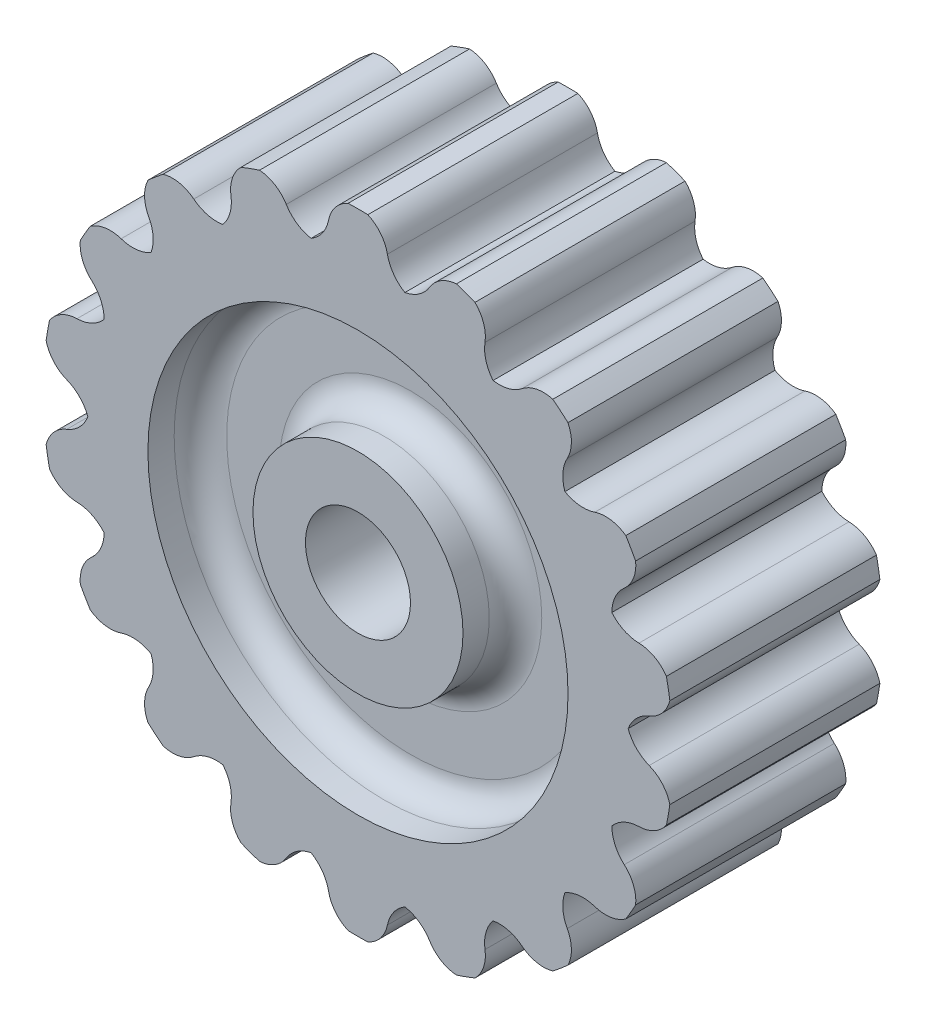
SolidWorks part; units mm, degrees
ref_plane "Front Plane" through (0, 0, 0) normal (0, 0, 1) x (1, 0, 0)
ref_plane "Top Plane" through (0, 0, 0) normal (0, 1, 0) x (1, 0, 0)
ref_plane "Right Plane" through (0, 0, 0) normal (1, 0, 0) x (0, 0, -1)
sketch "Sketch1" plane through (0, 0, 0) normal (1, 0, 0) x (0, 0, -1)
  line L0 (-45.5018, 0) -> (45.5018, 0) construction
  line L1 (0, 44.1006) -> (0, -44.1006) construction
  line L2 (-12.7, 6.35) -> (-12.7, 12.7)
  line L3 (-12.7, 12.7) -> (-9.525, 12.7)
  line L4 (-9.525, 12.7) -> (-9.525, 25.4)
  line L5 (-9.525, 25.4) -> (-12.7, 25.4)
  line L6 (-12.7, 25.4) -> (-12.7, 38.1)
  line L7 (-12.7, 38.1) -> (12.7, 38.1)
  line L8 (-12.7, 6.35) -> (12.7, 6.35)
  line L9 (-26.9876, 19.05) -> (7.3019, 19.05) construction
  line L10 (-6.35, 15.875) -> (-6.35, 22.225)
  line L11 (6.35, 15.875) -> (6.35, 22.225)
  line L12 (12.7, 25.4) -> (12.7, 38.1)
  line L13 (9.525, 25.4) -> (12.7, 25.4)
  line L14 (9.525, 12.7) -> (9.525, 25.4)
  line L15 (12.7, 12.7) -> (9.525, 12.7)
  line L16 (12.7, 6.35) -> (12.7, 12.7)
  arc A0 (-9.525, 25.4) -> (-6.35, 22.225) centre (-9.525, 22.225) cw
  arc A1 (-9.525, 12.7) -> (-6.35, 15.875) centre (-9.525, 15.875) ccw
  arc A2 (9.525, 12.7) -> (6.35, 15.875) centre (9.525, 15.875) cw
  arc A3 (9.525, 25.4) -> (6.35, 22.225) centre (9.525, 22.225) ccw
  point P4 (0, 0)
  point P8 (0, 0)
  point P15 (0, 6.35)
  point P18 (-6.35, 14.6295)
  point P22 (0, 44.1006)
  point P33 (0, 38.1)
  dimension "D4" = 3.175
  dimension "D7" = 6.35
  dimension "D9" = 3.175
  dimension "D1" = 6.35
  dimension "D2" = 25.4
  dimension "D3" = 6.35
  dimension "D5" = 25.4
  dimension "D6" = 12.7
  dimension "D8" = 12.7
  dimension "D10" = 12.7
revolve "Revolve1" add sketch "Sketch1" angle 360 about L0
sketch "Sketch2" plane through (0, 0, 12.7) normal (0, 0, 1) x (1, 0, 0)
  line L0 (0, 62.3351) -> (0, 0) construction
  circle A0 centre (0, 0) radius 32.6644
  circle A1 centre (0, 0) radius 35.306
  circle A2 centre (0, 0) radius 38.1 construction
  arc A3 (-5.6721, 32.1682) -> (-3.56, 35.1261) centre (-7.9287, 36.0125) ccw
  arc A4 (-3.56, 35.1261) -> (-1.1938, 38.0813) centre (0.4965, 34.303) cw
  arc A5 (3.56, 35.1261) -> (1.1938, 38.0813) centre (-0.4965, 34.303) ccw
  arc A6 (5.6721, 32.1682) -> (3.56, 35.1261) centre (7.9287, 36.0125) cw
  arc A7 (5.6721, 32.1682) -> (8.6685, 34.2253) centre (4.8665, 36.5524) ccw
  arc A8 (8.6685, 34.2253) -> (11.9028, 36.193) centre (12.1989, 32.0645) cw
  arc A9 (15.3591, 31.7901) -> (14.1464, 35.3764) centre (11.2658, 32.4041) ccw
  arc A10 (16.3322, 28.2882) -> (15.3591, 31.7901) centre (19.7675, 31.1289) cw
  arc A11 (16.3322, 28.2882) -> (19.8515, 29.1965) centre (17.0747, 32.6836) ccw
  arc A12 (19.8515, 29.1965) -> (23.5637, 29.9393) centre (22.4299, 25.9585) cw
  arc A13 (25.3057, 24.6198) -> (25.3927, 28.4046) centre (21.6692, 26.5967) ccw
  arc A14 (25.0224, 20.9963) -> (25.3057, 24.6198) centre (29.2221, 22.4907) cw
  arc A15 (25.0224, 20.9963) -> (28.64, 20.6461) centre (27.2234, 24.8726) ccw
  arc A16 (28.64, 20.6461) -> (32.3825, 20.0745) centre (29.9555, 16.7215) cw
  arc A17 (32.2001, 14.48) -> (33.5763, 18.0068) centre (29.459, 17.5815) ccw
  arc A18 (30.6945, 11.1719) -> (32.2001, 14.48) centre (35.152, 11.1398) cw
  arc A19 (30.6945, 11.1719) -> (33.9742, 9.6055) centre (34.0886, 14.0617) ccw
  arc A20 (33.9742, 9.6055) -> (37.2955, 7.7884) centre (33.8681, 5.4677) cw
  arc A21 (35.2106, 2.5936) -> (37.7101, 5.4371) centre (33.6956, 6.4456) ccw
  arc A22 (32.6644, 0) -> (35.2106, 2.5936) centre (36.8422, -1.5547) cw
  arc A23 (32.6644, 0) -> (35.2106, -2.5936) centre (36.8422, 1.5547) ccw
  arc A24 (35.2106, -2.5936) -> (37.7101, -5.4371) centre (33.6956, -6.4456) cw
  arc A25 (33.9742, -9.6055) -> (37.2955, -7.7884) centre (33.8681, -5.4677) ccw
  arc A26 (30.6945, -11.1719) -> (33.9742, -9.6055) centre (34.0886, -14.0617) cw
  arc A27 (30.6945, -11.1719) -> (32.2001, -14.48) centre (35.152, -11.1398) ccw
  arc A28 (32.2001, -14.48) -> (33.5763, -18.0068) centre (29.459, -17.5815) cw
  arc A29 (28.64, -20.6461) -> (32.3825, -20.0745) centre (29.9555, -16.7215) ccw
  arc A30 (25.0224, -20.9963) -> (28.64, -20.6461) centre (27.2234, -24.8726) cw
  arc A31 (25.0224, -20.9963) -> (25.3057, -24.6198) centre (29.2221, -22.4907) ccw
  arc A32 (25.3057, -24.6198) -> (25.3927, -28.4046) centre (21.6692, -26.5967) cw
  arc A33 (19.8515, -29.1965) -> (23.5637, -29.9393) centre (22.4299, -25.9585) ccw
  arc A34 (16.3322, -28.2882) -> (19.8515, -29.1965) centre (17.0747, -32.6836) cw
  arc A35 (16.3322, -28.2882) -> (15.3591, -31.7901) centre (19.7675, -31.1289) ccw
  arc A36 (15.3591, -31.7901) -> (14.1464, -35.3764) centre (11.2658, -32.4041) cw
  arc A37 (8.6685, -34.2253) -> (11.9028, -36.193) centre (12.1989, -32.0645) ccw
  arc A38 (5.6721, -32.1682) -> (8.6685, -34.2253) centre (4.8665, -36.5524) cw
  arc A39 (5.6721, -32.1682) -> (3.56, -35.1261) centre (7.9287, -36.0125) ccw
  arc A40 (3.56, -35.1261) -> (1.1938, -38.0813) centre (-0.4965, -34.303) cw
  arc A41 (-3.56, -35.1261) -> (-1.1938, -38.0813) centre (0.4965, -34.303) ccw
  arc A42 (-5.6721, -32.1682) -> (-3.56, -35.1261) centre (-7.9287, -36.0125) cw
  arc A43 (-5.6721, -32.1682) -> (-8.6685, -34.2253) centre (-4.8665, -36.5524) ccw
  arc A44 (-8.6685, -34.2253) -> (-11.9028, -36.193) centre (-12.1989, -32.0645) cw
  arc A45 (-15.3591, -31.7901) -> (-14.1464, -35.3764) centre (-11.2658, -32.4041) ccw
  arc A46 (-16.3322, -28.2882) -> (-15.3591, -31.7901) centre (-19.7675, -31.1289) cw
  arc A47 (-16.3322, -28.2882) -> (-19.8515, -29.1965) centre (-17.0747, -32.6836) ccw
  arc A48 (-19.8515, -29.1965) -> (-23.5637, -29.9393) centre (-22.4299, -25.9585) cw
  arc A49 (-25.3057, -24.6198) -> (-25.3927, -28.4046) centre (-21.6692, -26.5967) ccw
  arc A50 (-25.0224, -20.9963) -> (-25.3057, -24.6198) centre (-29.2221, -22.4907) cw
  arc A51 (-25.0224, -20.9963) -> (-28.64, -20.6461) centre (-27.2234, -24.8726) ccw
  arc A52 (-28.64, -20.6461) -> (-32.3825, -20.0745) centre (-29.9555, -16.7215) cw
  arc A53 (-32.2001, -14.48) -> (-33.5763, -18.0068) centre (-29.459, -17.5815) ccw
  arc A54 (-30.6945, -11.1719) -> (-32.2001, -14.48) centre (-35.152, -11.1398) cw
  arc A55 (-30.6945, -11.1719) -> (-33.9742, -9.6055) centre (-34.0886, -14.0617) ccw
  arc A56 (-33.9742, -9.6055) -> (-37.2955, -7.7884) centre (-33.8681, -5.4677) cw
  arc A57 (-35.2106, -2.5936) -> (-37.7101, -5.4371) centre (-33.6956, -6.4456) ccw
  arc A58 (-32.6644, 0) -> (-35.2106, -2.5936) centre (-36.8422, 1.5547) cw
  arc A59 (-32.6644, 0) -> (-35.2106, 2.5936) centre (-36.8422, -1.5547) ccw
  arc A60 (-35.2106, 2.5936) -> (-37.7101, 5.4371) centre (-33.6956, 6.4456) cw
  arc A61 (-33.9742, 9.6055) -> (-37.2955, 7.7884) centre (-33.8681, 5.4677) ccw
  arc A62 (-30.6945, 11.1719) -> (-33.9742, 9.6055) centre (-34.0886, 14.0617) cw
  arc A63 (-30.6945, 11.1719) -> (-32.2001, 14.48) centre (-35.152, 11.1398) ccw
  arc A64 (-32.2001, 14.48) -> (-33.5763, 18.0068) centre (-29.459, 17.5815) cw
  arc A65 (-28.64, 20.6461) -> (-32.3825, 20.0745) centre (-29.9555, 16.7215) ccw
  arc A66 (-25.0224, 20.9963) -> (-28.64, 20.6461) centre (-27.2234, 24.8726) cw
  arc A67 (-25.0224, 20.9963) -> (-25.3057, 24.6198) centre (-29.2221, 22.4907) ccw
  arc A68 (-25.3057, 24.6198) -> (-25.3927, 28.4046) centre (-21.6692, 26.5967) cw
  arc A69 (-19.8515, 29.1965) -> (-23.5637, 29.9393) centre (-22.4299, 25.9585) ccw
  arc A70 (-16.3322, 28.2882) -> (-19.8515, 29.1965) centre (-17.0747, 32.6836) cw
  arc A71 (-16.3322, 28.2882) -> (-15.3591, 31.7901) centre (-19.7675, 31.1289) ccw
  arc A72 (-15.3591, 31.7901) -> (-14.1464, 35.3764) centre (-11.2658, 32.4041) cw
  arc A73 (-8.6685, 34.2253) -> (-11.9028, 36.193) centre (-12.1989, 32.0645) ccw
  arc A74 (-5.6721, 32.1682) -> (-8.6685, 34.2253) centre (-4.8665, 36.5524) cw
  point P4 (0, 31.1675)
  point P5 (0, 0)
  point P7 (0, 31.1675)
  point P21 (4.7519, 32.3169)
  point P22 (0.9941, 38.087)
  point P23 (0, 0)
  point P24 (23.4416, 30.035)
  point P34 (0, 0)
  point P44 (0, 0)
  point P54 (0, 0)
  point P194 (0, 0)
  point P195 (0, 0)
  point P196 (0, 0)
  point P197 (-5.0588, 32.2703)
  dimension "D1" = 5.4356
  dimension "D2" = 70.612
  dimension "D3" = 2.3876
  dimension "D5" = 4.4577
  dimension "D6" = 4.1392
  dimension "D4" = 18
extrude "Cut-Extrude4" cut sketch "Sketch2" against normal through all both contours A1 A72 A3 A69 | A70 A71 A1 | A74 A3 A1 | A6 A7 A1 | A10 A11 A1 | A14 A15 A1 | A18 A19 A1 | A22 A23 A1 | A26 A27 A1 | A66 A67 A1 | A62 A63 A1 | A58 A59 A1 | A54 A55 A1 | A50 A51 A1 | A46 A47 A1 | A42 A43 A1 | A38 A39 A1 | A34 A35 A1 | A30 A31 A1 | A1 A28 A3 A25 | A1 A32 A3 A29 | A1 A36 A3 A33 | A1 A40 A3 A37 | A1 A44 A3 A41 | A1 A48 A3 A45 | A1 A52 A3 A49 | A1 A56 A3 A53 | A1 A60 A3 A57 | A1 A64 A3 A61 | A1 A68 A3 A65 | A1 A24 A3 A21 | A1 A20 A3 A17 | A1 A16 A3 A13 | A1 A12 A3 A9 | A73 A1 A4 A3 | A1 A8 A3 A5
